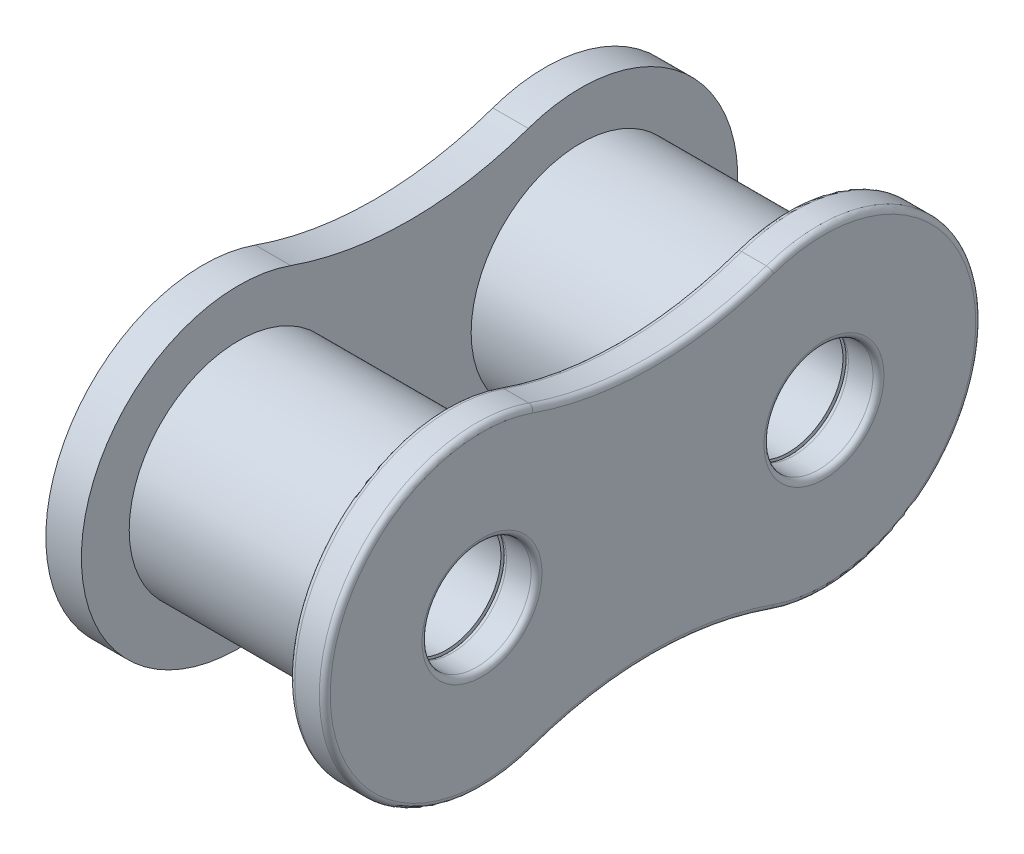
SolidWorks part; units mm, degrees
material "AISI 304"
ref_plane "Front Plane" through (0, 0, 0) normal (0, 0, 1) x (1, 0, 0)
ref_plane "Top Plane" through (0, 0, 0) normal (0, 1, 0) x (1, 0, 0)
ref_plane "Right Plane" through (0, 0, 0) normal (1, 0, 0) x (0, 0, -1)
sketch "Sketch1" plane through (0, 0, 0) normal (1, 0, 0) x (0, 0, -1)
  line L0 (0, 0) -> (0, 1901.7025) construction
  line L1 (0, 0) -> (-1901.7025, 0) construction
  arc A2 (-5.5139, 6.8859) -> (-5.5139, -6.8859) centre (-7.9375, 0) ccw
  circle A3 centre (-7.9375, 0) radius 2.53
  circle A4 centre (7.9375, 0) radius 2.53
  arc A5 (5.5139, 6.8859) -> (5.5139, -6.8859) centre (7.9375, 0) cw
  arc A6 (-5.5139, 6.8859) -> (5.5139, 6.8859) centre (0, 22.5517) ccw
  arc A7 (-5.5139, -6.8859) -> (5.5139, -6.8859) centre (0, -22.5517) cw
  dimension "D1" = 14.6
  dimension "D2" = 5.06
  dimension "D3" = 7.9375
extrude "Boss-Extrude1" add sketch "Sketch1" along normal blind 1.65
fillet "Fillet1" radius 0.254 12 edges at (1.65, 0, -5.4075) (1.65, 0, -15.2375) (1.65, -5.9439, 0) (1.65, 0, 15.2375) (1.65, 5.9439, 0) (1.65, 0, 5.4075) (0, 0, -5.4075) (0, 0, 5.4075) (0, 0, 15.2375) (0, -5.9439, 0) (0, 0, -15.2375) (0, 5.9439, 0)
sketch "Sketch2" plane through (0, 0, 0) normal (-1, 0, 0) x (0, 0, 1)
  circle A0 centre (-7.9375, 0) radius 2.53 construction
  circle A1 centre (-7.9375, 0) radius 2.53
  circle A2 centre (-7.9375, 0) radius 5.08
extrude "Boss-Extrude2" add sketch "Sketch2" along normal blind 9.65
mirror "Mirror2" about plane through (0, 0, 0) normal (0, 0, 1) of "Boss-Extrude2"
ref_plane "Plane1" through (-4.825, 0, 0) normal (-1, 0, 0) x (0, 0, 1)
mirror "Mirror3" about plane through (-4.825, 0, 0) normal (-1, 0, 0) of "Boss-Extrude1"
